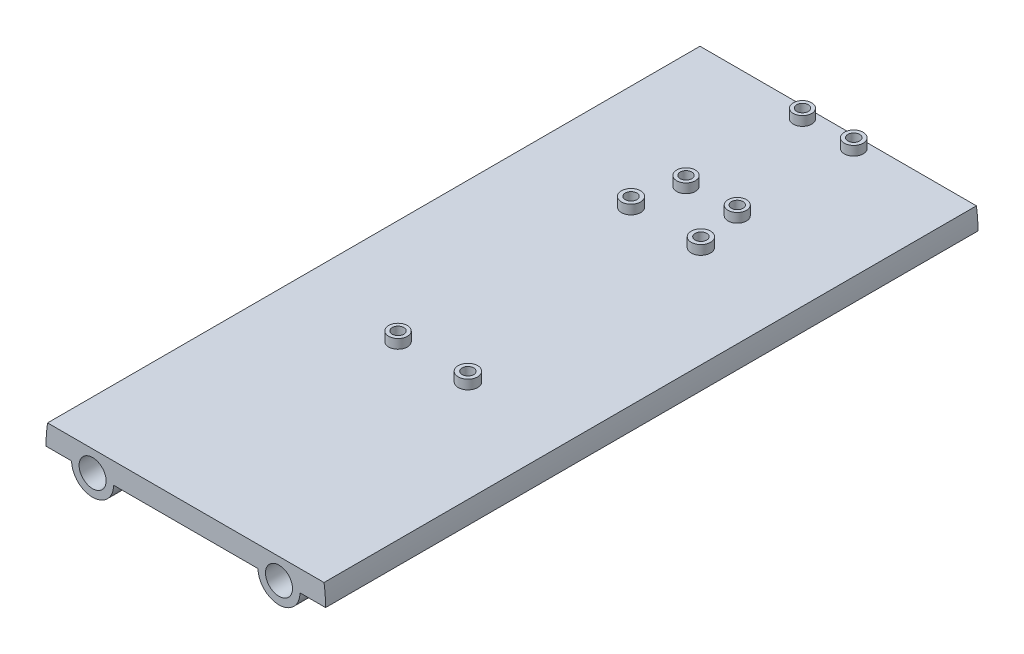
SolidWorks part; units mm, degrees
ref_plane "Front Plane" through (0, 0, 0) normal (0, 0, 1) x (1, 0, 0)
ref_plane "Top Plane" through (0, 0, 0) normal (0, 1, 0) x (1, 0, 0)
ref_plane "Right Plane" through (0, 0, 0) normal (1, 0, 0) x (0, 0, -1)
sketch "Sketch1" plane through (0, 0, 0) normal (0, 0, 1) x (1, 0, 0)
  line L0 (-25.4, 5.715) -> (25.4, 5.715)
  line L1 (-19.685, 0) -> (19.685, 0)
  line L2 (-25.4, 5.715) -> (-37.6689, 5.715)
  line L3 (25.4, 5.715) -> (37.6689, 5.715)
  line L4 (-31.115, 0) -> (-38.1, 0)
  line L5 (31.115, 0) -> (38.1, 0)
  circle A0 centre (25.4, 0) radius 3.683
  circle A1 centre (-25.4, 0) radius 3.683
  circle A2 centre (-25.4, 0) radius 5.715
  circle A3 centre (25.4, 0) radius 5.715
  circle A4 centre (0, 0) radius 38.1
  dimension "D3" = 7.366
  dimension "D4" = 11.43
  dimension "D5" = 11.43
  dimension "D6" = 76.2
  dimension "D1" = 25.4
  dimension "D2" = 25.4
extrude "Boss-Extrude2" add sketch "Sketch1" along normal blind 177.8 contours A3 L0 A2 L1 | A2 A1 | A3 A0 | L2 A4 L4 A2 | L5 A4 L3 A3
sketch "Sketch2" plane through (0, 5.715, 0) normal (0, 1, 0) x (1, 0, 0)
  line L0 (-37.6689, 0) -> (37.6689, 0) construction
  line L1 (-37.6689, -177.8) -> (-37.6689, 0) construction
  circle A0 centre (-6.5539, -3.175) radius 1.5875
  circle A1 centre (7.4161, -3.175) radius 1.5875
  circle A2 centre (-6.5539, -34.925) radius 1.5875
  circle A3 centre (7.4161, -34.925) radius 1.5875
  dimension "D4" = 3.175
  dimension "D1" = 31.75
  dimension "D2" = 31.75
  dimension "D3" = 13.97
  dimension "D5" = 3.175
  dimension "D6" = 31.115
extrude "Cut-Extrude1" cut sketch "Sketch2" against normal through all
sketch "Sketch3" plane through (0, 5.715, 0) normal (0, 1, 0) x (1, 0, 0)
  circle A0 centre (-6.5539, -3.175) radius 2.5217
  circle A1 centre (7.4161, -3.175) radius 2.5806
  circle A2 centre (7.4161, -34.925) radius 2.5136
  circle A3 centre (-6.5539, -34.925) radius 2.5381
  circle A4 centre (-6.5539, -3.175) radius 1.5875
  circle A5 centre (7.4161, -3.175) radius 1.5875
  circle A6 centre (-6.5539, -34.925) radius 1.5875
  circle A7 centre (7.4161, -34.925) radius 1.5875
extrude "Boss-Extrude4" add sketch "Sketch3" along normal blind 2.54
sketch "Sketch4" plane through (0, 5.715, 0) normal (0, 1, 0) x (1, 0, 0)
  line L0 (-37.6689, -177.8) -> (-37.6689, 0) construction
  circle A0 centre (-9.0939, -47.3684) radius 1.5875
  circle A1 centre (9.9561, -47.3684) radius 1.5875
  circle A2 centre (9.9561, -110.8684) radius 1.5875
  circle A3 centre (-9.0939, -110.8684) radius 1.5875
  circle A4 centre (-6.5539, -34.925) radius 1.5875 construction
  point P10 (0, 0)
  dimension "D4" = 3.175
  dimension "D1" = 63.5
  dimension "D2" = 63.5
  dimension "D3" = 12.7
  dimension "D5" = 19.05
  dimension "D6" = 28.575
extrude "Cut-Extrude2" cut sketch "Sketch4" against normal through all
sketch "Sketch5" plane through (0, 5.715, 0) normal (0, 1, 0) x (1, 0, 0)
  circle A0 centre (-9.0939, -47.3684) radius 1.5875
  circle A1 centre (9.9561, -47.3684) radius 1.5875
  circle A2 centre (9.9561, -110.8684) radius 1.5875
  circle A3 centre (-9.0939, -110.8684) radius 1.5875
  circle A4 centre (-9.0939, -47.3684) radius 2.6189
  circle A5 centre (9.9561, -47.3684) radius 2.6395
  circle A6 centre (9.9561, -110.8684) radius 2.6481
  circle A7 centre (-9.0939, -110.8684) radius 2.5502
extrude "Boss-Extrude5" add sketch "Sketch5" along normal blind 2.54
